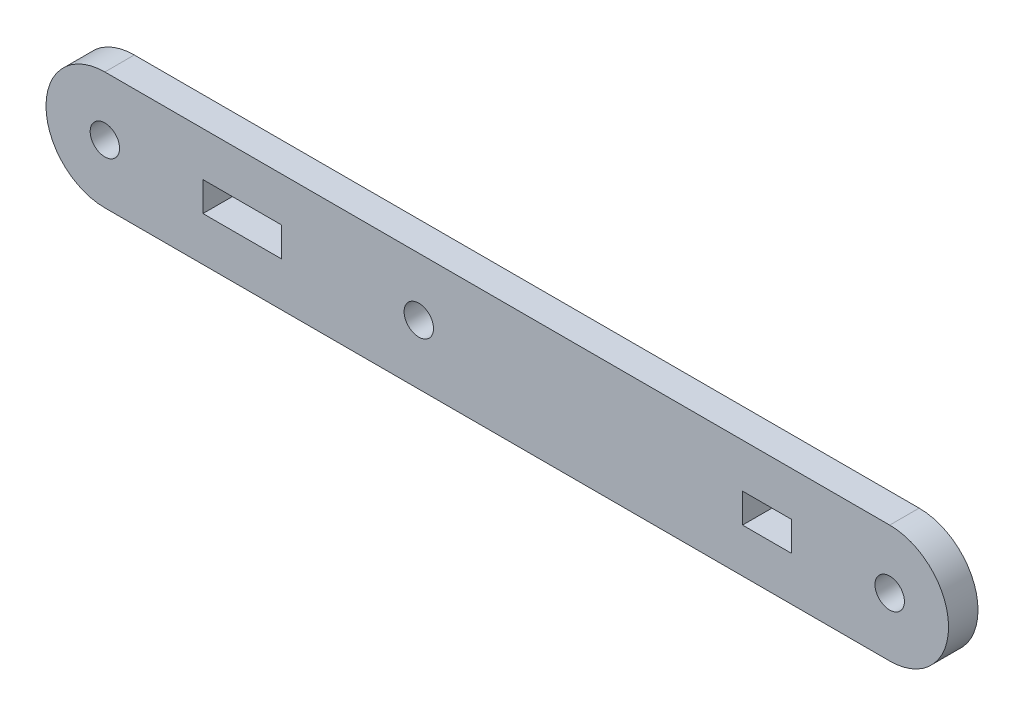
SolidWorks part; units mm, degrees
ref_plane "Plan de face" through (0, 0, 0) normal (0, 0, 1) x (1, 0, 0)
ref_plane "Plan de dessus" through (0, 0, 0) normal (0, 1, 0) x (1, 0, 0)
ref_plane "Plan de droite" through (0, 0, 0) normal (1, 0, 0) x (0, 0, -1)
sketch "Esquisse8" plane through (0, 0, 0) normal (0, 0, 1) x (1, 0, 0)
  line L0 (-62.9738, -40.5517) -> (17.0262, -40.5517) construction
  line L1 (-62.9738, -34.5517) -> (17.0262, -34.5517)
  line L2 (-62.9738, -46.5517) -> (17.0262, -46.5517)
  line L4 (-52.9738, -42.0517) -> (-44.9738, -42.0517)
  line L5 (-52.9738, -42.0517) -> (-52.9738, -39.0517)
  line L6 (-52.9738, -39.0517) -> (-44.9738, -39.0517)
  line L7 (-44.9738, -42.0517) -> (-44.9738, -39.0517)
  line L8 (2.0262, -42.0517) -> (7.0262, -42.0517)
  line L9 (2.0262, -42.0517) -> (2.0262, -39.0517)
  line L10 (2.0262, -39.0517) -> (7.0262, -39.0517)
  line L11 (7.0262, -42.0517) -> (7.0262, -39.0517)
  circle A0 centre (-62.9738, -40.5517) radius 1.5
  circle A1 centre (-30.9738, -40.4576) radius 1.5
  circle A2 centre (17.0262, -40.5517) radius 1.5
  arc A3 (-62.9738, -34.5517) -> (-62.9738, -46.5517) centre (-62.9738, -40.5517) ccw
  arc A4 (17.0262, -46.5517) -> (17.0262, -34.5517) centre (17.0262, -40.5517) ccw
  point P6 (-22.9738, -40.5517)
  dimension "D1" = 6
  dimension "D2" = 3
  dimension "D3" = 3
  dimension "D4" = 3
  dimension "D5" = 80
  dimension "D6" = 8
  dimension "D7" = 5
  dimension "D8" = 3
  dimension "D9" = 1.5
  dimension "D10" = 1.5
  dimension "D11" = 3
  dimension "D12" = 47
  dimension "D13" = 10
  dimension "D14" = 14
extrude "Boss.-Extru.8" add sketch "Esquisse8" along normal blind 3 separate body
